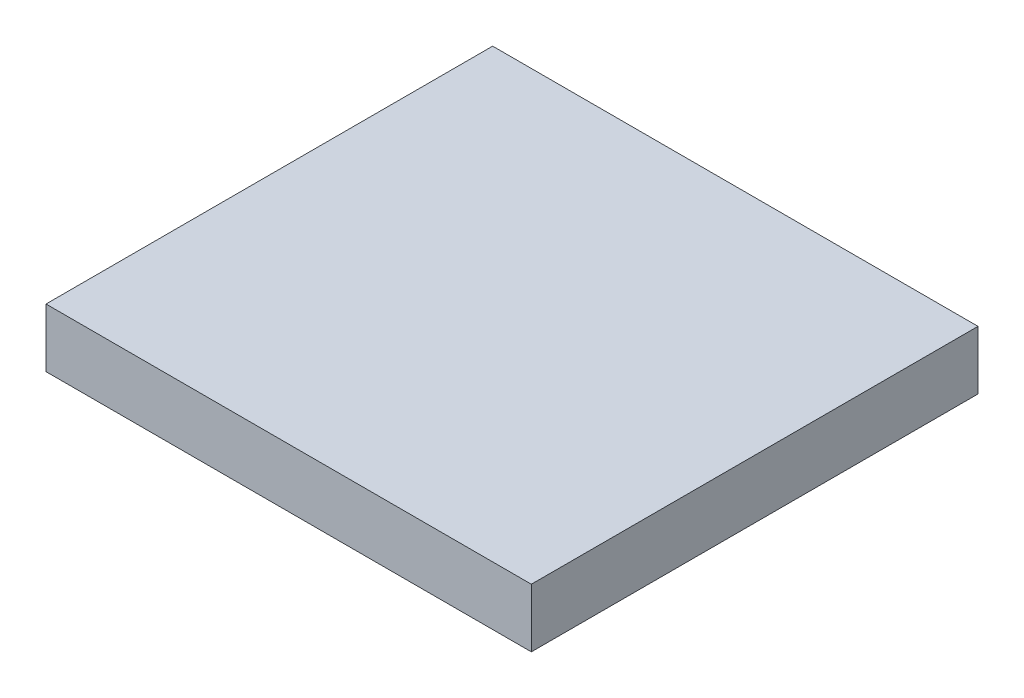
SolidWorks part; units mm, degrees
ref_plane "前视基准面" through (0, 0, 0) normal (0, 0, 1) x (1, 0, 0)
ref_plane "上视基准面" through (0, 0, 0) normal (0, 1, 0) x (1, 0, 0)
ref_plane "右视基准面" through (0, 0, 0) normal (1, 0, 0) x (0, 0, -1)
sketch "草图1" plane through (0, 0, 0) normal (0, 1, 0) x (1, 0, 0)
  line L1 (0, 0) -> (2070, 0)
  line L2 (0, 0) -> (0, 1905)
  line L3 (0, 1905) -> (2070, 1905)
  line L4 (2070, 0) -> (2070, 1905)
extrude "凸台-拉伸1" add sketch "草图1" along normal blind 249.9124
